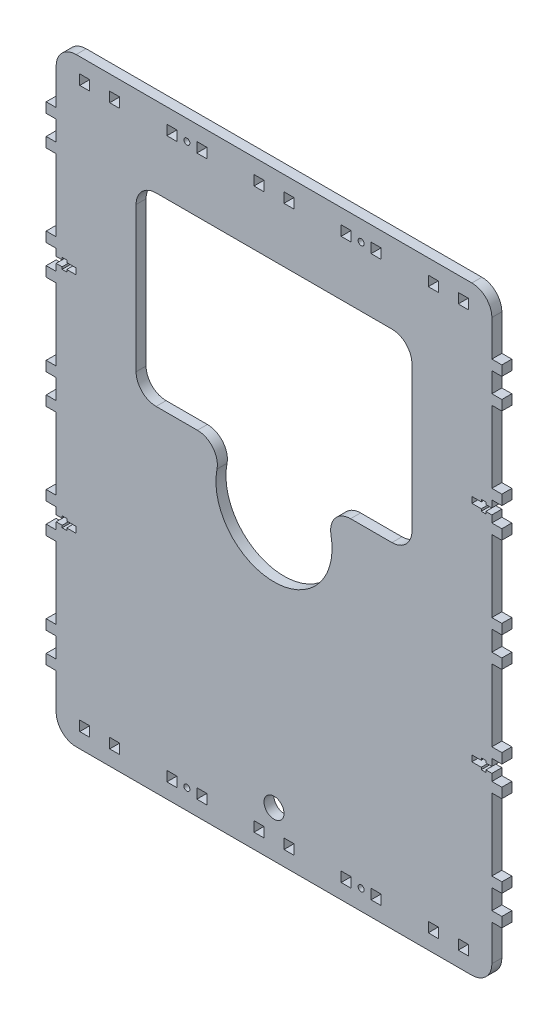
SolidWorks part; units mm, degrees
ref_plane "Front Plane" through (0, 0, 0) normal (0, 0, 1) x (1, 0, 0)
ref_plane "Top Plane" through (0, 0, 0) normal (0, 1, 0) x (1, 0, 0)
ref_plane "Right Plane" through (0, 0, 0) normal (1, 0, 0) x (0, 0, -1)
sketch "Sketch1" plane through (0, 0, 0) normal (0, 0, 1) x (1, 0, 0)
  line L0 (-109, -140) -> (109, -140) construction
  line L1 (109, 140) -> (109, 122)
  line L2 (-92.2, -140) -> (-82.2, -140) construction
  line L3 (-109, 140) -> (109, 140) construction
  line L5 (-92.2, -137.5) -> (-97.2, -137.5)
  line L6 (-92.2, -137.5) -> (-92.2, -142.5)
  line L7 (-99, -150) -> (99, -150)
  line L8 (-92.2, -142.5) -> (-97.2, -142.5)
  line L9 (-97.2, -137.5) -> (-97.2, -142.5)
  line L10 (-82.2, -137.5) -> (-77.2, -137.5)
  line L11 (-82.2, -137.5) -> (-82.2, -142.5)
  line L12 (-82.2, -142.5) -> (-77.2, -142.5)
  line L13 (-77.2, -137.5) -> (-77.2, -142.5)
  line L14 (-87.2, -140) -> (-87.2, -133.0276) construction
  line L15 (-48.6, -140) -> (-38.6, -140) construction
  line L16 (-109, -140) -> (-109, -122)
  line L17 (-99, 150) -> (99, 150)
  line L19 (-48.6, -137.5) -> (-53.6, -137.5)
  line L20 (-48.6, -137.5) -> (-48.6, -142.5)
  line L21 (-48.6, -142.5) -> (-53.6, -142.5)
  line L22 (-53.6, -137.5) -> (-53.6, -142.5)
  line L23 (-38.6, -137.5) -> (-33.6, -137.5)
  line L24 (-38.6, -137.5) -> (-38.6, -142.5)
  line L25 (-38.6, -142.5) -> (-33.6, -142.5)
  line L26 (-33.6, -137.5) -> (-33.6, -142.5)
  line L27 (-43.6, -140) -> (-43.6, -133.0276) construction
  line L28 (-5, -140) -> (5, -140) construction
  line L30 (-5, -137.5) -> (-10, -137.5)
  line L32 (-5, -137.5) -> (-5, -142.5)
  line L33 (-5, -142.5) -> (-10, -142.5)
  line L34 (-10, -137.5) -> (-10, -142.5)
  line L35 (5, -137.5) -> (10, -137.5)
  line L36 (5, -137.5) -> (5, -142.5)
  line L37 (5, -142.5) -> (10, -142.5)
  line L38 (10, -137.5) -> (10, -142.5)
  line L39 (0, -140) -> (0, -133.0276) construction
  line L40 (38.6, -140) -> (48.6, -140) construction
  line L41 (38.6, -137.5) -> (33.6, -137.5)
  line L42 (38.6, -137.5) -> (38.6, -142.5)
  line L43 (38.6, -142.5) -> (33.6, -142.5)
  line L44 (33.6, -137.5) -> (33.6, -142.5)
  line L45 (48.6, -137.5) -> (53.6, -137.5)
  line L46 (48.6, -137.5) -> (48.6, -142.5)
  line L47 (48.6, -142.5) -> (53.6, -142.5)
  line L48 (-109, -108) -> (-109, -117)
  line L49 (53.6, -137.5) -> (53.6, -142.5)
  line L50 (0, 182.823) -> (0, -174.5679) construction
  line L51 (43.6, -140) -> (43.6, -133.0276) construction
  line L52 (82.2, -140) -> (92.2, -140) construction
  line L53 (82.2, -137.5) -> (77.2, -137.5)
  line L54 (82.2, -137.5) -> (82.2, -142.5)
  line L55 (82.2, -142.5) -> (77.2, -142.5)
  line L56 (77.2, -137.5) -> (77.2, -142.5)
  line L57 (92.2, -137.5) -> (97.2, -137.5)
  line L58 (92.2, -137.5) -> (92.2, -142.5)
  line L59 (92.2, -142.5) -> (97.2, -142.5)
  line L60 (97.2, -137.5) -> (97.2, -142.5)
  line L61 (87.2, -140) -> (87.2, -133.0276) construction
  line L62 (-129.5738, 0) -> (-109, 0) construction
  line L63 (82.2, 140) -> (92.2, 140) construction
  line L64 (38.6, 140) -> (48.6, 140) construction
  line L65 (-5, 140) -> (5, 140) construction
  line L66 (-48.6, 140) -> (-38.6, 140) construction
  line L67 (-92.2, 140) -> (-82.2, 140) construction
  line L68 (97.2, 137.5) -> (97.2, 142.5)
  line L70 (92.2, 142.5) -> (97.2, 142.5)
  line L71 (92.2, 137.5) -> (92.2, 142.5)
  line L73 (92.2, 137.5) -> (97.2, 137.5)
  line L74 (77.2, 137.5) -> (77.2, 142.5)
  line L77 (82.2, 142.5) -> (77.2, 142.5)
  line L78 (82.2, 137.5) -> (82.2, 142.5)
  line L79 (82.2, 137.5) -> (77.2, 137.5)
  line L80 (53.6, 137.5) -> (53.6, 142.5)
  line L81 (48.6, 142.5) -> (53.6, 142.5)
  line L82 (48.6, 137.5) -> (48.6, 142.5)
  line L84 (48.6, 137.5) -> (53.6, 137.5)
  line L86 (33.6, 137.5) -> (33.6, 142.5)
  line L89 (38.6, 142.5) -> (33.6, 142.5)
  line L92 (38.6, 137.5) -> (38.6, 142.5)
  line L93 (38.6, 137.5) -> (33.6, 137.5)
  line L94 (10, 137.5) -> (10, 142.5)
  line L95 (5, 142.5) -> (10, 142.5)
  line L97 (5, 137.5) -> (5, 142.5)
  line L98 (5, 137.5) -> (10, 137.5)
  line L99 (-10, 137.5) -> (-10, 142.5)
  line L100 (-5, 142.5) -> (-10, 142.5)
  line L101 (-5, 137.5) -> (-5, 142.5)
  line L102 (-5, 137.5) -> (-10, 137.5)
  line L103 (-33.6, 137.5) -> (-33.6, 142.5)
  line L104 (-38.6, 142.5) -> (-33.6, 142.5)
  line L105 (-38.6, 137.5) -> (-38.6, 142.5)
  line L106 (-38.6, 137.5) -> (-33.6, 137.5)
  line L107 (-53.6, 137.5) -> (-53.6, 142.5)
  line L108 (-48.6, 142.5) -> (-53.6, 142.5)
  line L109 (-48.6, 137.5) -> (-48.6, 142.5)
  line L110 (-48.6, 137.5) -> (-53.6, 137.5)
  line L111 (-77.2, 137.5) -> (-77.2, 142.5)
  line L112 (-82.2, 142.5) -> (-77.2, 142.5)
  line L113 (-82.2, 137.5) -> (-82.2, 142.5)
  line L114 (-82.2, 137.5) -> (-77.2, 137.5)
  line L115 (-97.2, 137.5) -> (-97.2, 142.5)
  line L116 (-92.2, 142.5) -> (-97.2, 142.5)
  line L117 (-92.2, 137.5) -> (-92.2, 142.5)
  line L118 (-92.2, 137.5) -> (-97.2, 137.5)
  line L119 (109, 0) -> (97.7792, 0) construction
  line L120 (59, -110) -> (-59, -110) construction
  line L121 (69, -100) -> (69, 100) construction
  line L122 (59, 110) -> (-59, 110) construction
  line L123 (-69, -100) -> (-69, 100) construction
  line L124 (69, -110) -> (-69, 110) construction
  line L125 (69, 110) -> (-69, -110) construction
  line L126 (109, -1.5) -> (109, -5)
  line L127 (114, -5) -> (114, -10)
  line L128 (114, -10) -> (109, -10)
  line L129 (114, -5) -> (109, -5)
  line L130 (109, 1.5) -> (109, 5)
  line L131 (109, 5) -> (114, 5)
  line L132 (114, 5) -> (114, 10)
  line L133 (114, 10) -> (109, 10)
  line L134 (109, -1.5) -> (109, 1.5) construction
  line L135 (109, 5) -> (109, -5)
  line L136 (109, -10) -> (109, -46)
  line L137 (109, -51) -> (109, -54.5)
  line L138 (109, -66) -> (109, -102)
  line L139 (109, -57.5) -> (109, -61)
  line L140 (109, -122) -> (109, -140)
  line L141 (109, -107) -> (109, -117)
  line L142 (-109, 122) -> (-109, 140)
  line L143 (-109, 117) -> (-109, 107)
  line L144 (-109, 107) -> (-109, 117)
  line L145 (-109, 102) -> (-109, 66)
  line L146 (99, 0) -> (109, 0) construction
  line L147 (109, 56) -> (95.1587, 56) construction
  line L148 (109, 54.5) -> (109, 51)
  line L149 (114, 51) -> (114, 46)
  line L150 (114, 46) -> (109, 46)
  line L151 (114, 51) -> (109, 51)
  line L152 (109, 57.5) -> (109, 61)
  line L153 (109, 61) -> (114, 61)
  line L154 (114, 61) -> (114, 66)
  line L155 (114, 66) -> (109, 66)
  line L156 (109, 54.5) -> (109, 57.5) construction
  line L157 (109, 57.5) -> (106, 57.5)
  line L158 (103.7, 57.5) -> (103.7, 58.6)
  line L159 (106, 53.4) -> (103.7, 53.4)
  line L160 (106, 58.6) -> (106, 57.5)
  line L161 (103.7, 57.5) -> (99, 57.5)
  line L162 (99, 57.5) -> (99, 54.5)
  line L163 (99, 54.5) -> (103.7, 54.5)
  line L164 (106, 54.5) -> (106, 53.4)
  line L165 (103.7, 58.6) -> (106, 58.6)
  line L166 (103.7, 53.4) -> (103.7, 54.5)
  line L167 (106, 54.5) -> (109, 54.5)
  line L168 (99, 56) -> (109, 56) construction
  line L169 (109, 113.5) -> (109, 110.5)
  line L170 (109, 110.5) -> (109, 107)
  line L171 (114, 107) -> (114, 102)
  line L172 (114, 102) -> (109, 102)
  line L173 (114, 107) -> (109, 107)
  line L174 (109, 113.5) -> (109, 117)
  line L175 (109, 117) -> (114, 117)
  line L176 (114, 117) -> (114, 122)
  line L177 (114, 122) -> (109, 122)
  line L178 (109, 110.5) -> (109, 113.5) construction
  line L179 (109, 102) -> (109, 66)
  line L180 (-109, 66) -> (-109, 102)
  line L181 (-109, 61) -> (-109, 57.5)
  line L182 (-109, 51) -> (-109, 54.5)
  line L183 (-109, 46) -> (-109, 10)
  line L184 (-109, 54.5) -> (-109, 51)
  line L185 (-109, 57.5) -> (-109, 61)
  line L186 (-109, 10) -> (-109, 46)
  line L187 (-109, 5) -> (-109, -5)
  line L188 (-69, 0) -> (129.5738, 0) construction
  line L189 (-109, -5) -> (-109, 5)
  line L190 (-109, -10) -> (-109, -46)
  line L191 (-109, -46) -> (-109, -10)
  line L192 (109, -110.5) -> (109, -113.5) construction
  line L193 (81.3867, -112) -> (79.0545, -112) construction
  line L194 (-109, -51) -> (-109, -54.5)
  line L195 (-109, -61) -> (-109, -57.5)
  line L196 (99, -56) -> (95.1587, -56) construction
  line L197 (-109, -66) -> (-109, -102)
  line L198 (-109, -57.5) -> (-109, -61)
  line L199 (-109, -54.5) -> (-109, -51)
  line L200 (-109, -102) -> (-109, -66)
  line L201 (-109, -107) -> (-109, -117)
  line L202 (-109, -117) -> (-109, -107)
  line L203 (-109, -122) -> (-109, -150)
  line L204 (-109, -122) -> (-109, -140)
  line L205 (109, 102) -> (109, 66)
  line L206 (109, 61) -> (109, 51)
  line L207 (109, 46) -> (109, 10)
  line L208 (114, -122) -> (109, -122)
  line L209 (114, -117) -> (114, -122)
  line L210 (109, -117) -> (114, -117)
  line L211 (109, -113.5) -> (109, -117)
  line L212 (114, -107) -> (109, -107)
  line L213 (114, -102) -> (109, -102)
  line L214 (114, -107) -> (114, -102)
  line L215 (109, -110.5) -> (109, -107)
  line L216 (106, -54.5) -> (109, -54.5)
  line L217 (103.7, -53.4) -> (103.7, -54.5)
  line L218 (103.7, -58.6) -> (106, -58.6)
  line L219 (106, -54.5) -> (106, -53.4)
  line L220 (99, -54.5) -> (103.7, -54.5)
  line L221 (99, -57.5) -> (99, -54.5)
  line L222 (103.7, -57.5) -> (99, -57.5)
  line L223 (106, -58.6) -> (106, -57.5)
  line L224 (106, -53.4) -> (103.7, -53.4)
  line L225 (103.7, -57.5) -> (103.7, -58.6)
  line L226 (109, -57.5) -> (106, -57.5)
  line L227 (114, -66) -> (109, -66)
  line L228 (114, -61) -> (114, -66)
  line L229 (-109, -150) -> (69, 94.9541) construction
  line L230 (-109, 150) -> (109, -150) construction
  line L231 (109, -61) -> (114, -61)
  line L232 (109, -57.5) -> (109, -61)
  line L233 (114, -51) -> (109, -51)
  line L234 (114, -46) -> (109, -46)
  line L235 (114, -51) -> (114, -46)
  line L236 (109, -54.5) -> (109, -51)
  line L237 (-99, -56) -> (-95.1587, -56) construction
  line L238 (-23.1847, 17.5139) -> (-69, 17.5139)
  line L239 (-69, 17.5139) -> (-69, 110)
  line L240 (-69, 110) -> (69, 110)
  line L241 (-109, -110.5) -> (-109, -113.5) construction
  line L242 (69, 110) -> (69, 17.5139)
  line L243 (69, 17.5139) -> (23.1847, 17.5139)
  line L244 (-109, 110.5) -> (-109, 113.5) construction
  line L248 (-99, 56) -> (-95.1587, 56) construction
  line L250 (-109, -1.5) -> (-109, 1.5) construction
  line L252 (-109, -54.5) -> (-109, -51)
  line L253 (-114, -51) -> (-114, -46)
  line L254 (-114, -46) -> (-109, -46)
  line L255 (-114, -51) -> (-109, -51)
  line L256 (-109, -57.5) -> (-109, -61)
  line L257 (-109, -61) -> (-114, -61)
  line L258 (-114, -61) -> (-114, -66)
  line L259 (-114, -66) -> (-109, -66)
  line L260 (-109, -57.5) -> (-106, -57.5)
  line L261 (-103.7, -57.5) -> (-103.7, -58.6)
  line L262 (-106, -53.4) -> (-103.7, -53.4)
  line L263 (-106, -58.6) -> (-106, -57.5)
  line L264 (-103.7, -57.5) -> (-99, -57.5)
  line L265 (-99, -57.5) -> (-99, -54.5)
  line L266 (-99, -54.5) -> (-103.7, -54.5)
  line L267 (-106, -54.5) -> (-106, -53.4)
  line L268 (-103.7, -58.6) -> (-106, -58.6)
  line L269 (-103.7, -53.4) -> (-103.7, -54.5)
  line L270 (-106, -54.5) -> (-109, -54.5)
  line L271 (-109, -110.5) -> (-109, -107)
  line L272 (-114, -107) -> (-114, -102)
  line L273 (-114, -102) -> (-109, -102)
  line L274 (-114, -107) -> (-109, -107)
  line L275 (-109, -113.5) -> (-109, -117)
  line L276 (-109, -117) -> (-114, -117)
  line L277 (-114, -117) -> (-114, -122)
  line L278 (-114, -122) -> (-109, -122)
  line L301 (-114, 122) -> (-109, 122)
  line L302 (-114, 117) -> (-114, 122)
  line L303 (-109, 117) -> (-114, 117)
  line L304 (-109, 113.5) -> (-109, 117)
  line L305 (-114, 107) -> (-109, 107)
  line L306 (-114, 102) -> (-109, 102)
  line L307 (-114, 107) -> (-114, 102)
  line L308 (-109, 110.5) -> (-109, 107)
  line L309 (-106, 54.5) -> (-109, 54.5)
  line L310 (-103.7, 53.4) -> (-103.7, 54.5)
  line L311 (-103.7, 58.6) -> (-106, 58.6)
  line L312 (-106, 54.5) -> (-106, 53.4)
  line L313 (-99, 54.5) -> (-103.7, 54.5)
  line L314 (-99, 57.5) -> (-99, 54.5)
  line L315 (-103.7, 57.5) -> (-99, 57.5)
  line L316 (-106, 58.6) -> (-106, 57.5)
  line L317 (-106, 53.4) -> (-103.7, 53.4)
  line L318 (-103.7, 57.5) -> (-103.7, 58.6)
  line L319 (-109, 57.5) -> (-106, 57.5)
  line L320 (-114, 66) -> (-109, 66)
  line L321 (-114, 61) -> (-114, 66)
  line L322 (-109, 61) -> (-114, 61)
  line L323 (-109, 57.5) -> (-109, 61)
  line L324 (-114, 51) -> (-109, 51)
  line L325 (-114, 46) -> (-109, 46)
  line L326 (-114, 51) -> (-114, 46)
  line L327 (-109, 54.5) -> (-109, 51)
  line L339 (-114, 10) -> (-109, 10)
  line L340 (-114, 5) -> (-114, 10)
  line L341 (-109, 5) -> (-114, 5)
  line L342 (-109, 1.5) -> (-109, 5)
  line L343 (-114, -5) -> (-109, -5)
  line L344 (-114, -10) -> (-109, -10)
  line L345 (-114, -5) -> (-114, -10)
  line L346 (-109, -1.5) -> (-109, -5)
  line L347 (-109, 150) -> (-109, 122)
  line L348 (109, 117) -> (109, 107)
  line L349 (101.7333, 140) -> (109, 150) construction
  circle A1 centre (0, -126.8749) radius 5
  circle A3 centre (-43.6, -140) radius 1.5
  circle A5 centre (43.6, -140) radius 1.5
  circle A7 centre (43.6, 140) radius 1.5
  circle A8 centre (-43.6, 140) radius 1.5
  arc A9 (-59, -110) -> (-69, -100) centre (-59, -100) cw construction
  arc A10 (69, -100) -> (59, -110) centre (59, -100) cw construction
  arc A11 (69, 100) -> (59, 110) centre (59, 100) ccw construction
  arc A12 (-59, 110) -> (-69, 100) centre (-59, 100) ccw construction
  arc A13 (-99, -150) -> (-109, -140) centre (-99, -140) cw
  arc A14 (109, -140) -> (99, -150) centre (99, -140) cw
  arc A15 (109, 140) -> (99, 150) centre (99, 140) ccw
  arc A16 (-99, 150) -> (-109, 140) centre (-99, 140) ccw
  arc A17 (-23.1847, 17.5139) -> (23.1847, 17.5139) centre (0, 0) ccw
  point P39 (0, 0)
  point P219 (0, 0)
  point P292 (0, 0)
  dimension "D4" = 10
  dimension "D5" = 43.6
  dimension "D3" = 280
  dimension "D7" = 43.6
  dimension "D10" = 10
  dimension "D14" = 3
  dimension "D18" = 5
  dimension "D22" = 3
  dimension "D26" = 5
  dimension "D31" = 10
  dimension "D1" = 218
  dimension "D2" = 10
  dimension "D6" = 43.6
  dimension "D8" = 43.6
  dimension "D9" = 5
  dimension "D11" = 5
  dimension "D12" = 10
  dimension "D13" = 5
  dimension "D15" = 5
  dimension "D16" = 10
  dimension "D17" = 5
  dimension "D19" = 5
  dimension "D20" = 10
  dimension "D21" = 5
  dimension "D23" = 5
  dimension "D24" = 10
  dimension "D25" = 5
  dimension "D27" = 5
  dimension "D28" = 10
  dimension "D29" = 40
  dimension "D30" = 40
  dimension "D34" = 10
  dimension "D35" = 5
  dimension "D36" = 5
  dimension "D37" = 5.2
  dimension "D38" = 3
  dimension "D39" = 2.3
  dimension "D40" = 3
  dimension "D41" = 10
  dimension "D42" = 10
  dimension "D43" = 5
  dimension "D44" = 5
  dimension "D50" = 56
extrude "Boss-Extrude5" add sketch "Sketch1" along normal blind 5 contours L343 L345 L344 L190 L254 L253 L255 L194 L270 L267 L262 L269 L266 L265 L264 L261 L268 L263 L260 L195 L257 L258 L259 L197 L273 L272 L274 L201 L48 L202 L276 L277 L278 L203 L16 L7 L140 L208 L209 L210 L141 L212 L214 L213 L138 L227 L228 L231
fillet "Fillet1" radius 10 6 edges at (-23.1847, 17.5139, 2.5) (23.1847, 17.5139, 2.5) (69, 17.5139, 2.5) (-69, 110, 2.5) (69, 110, 2.5) (-69, 17.5139, 2.5)
